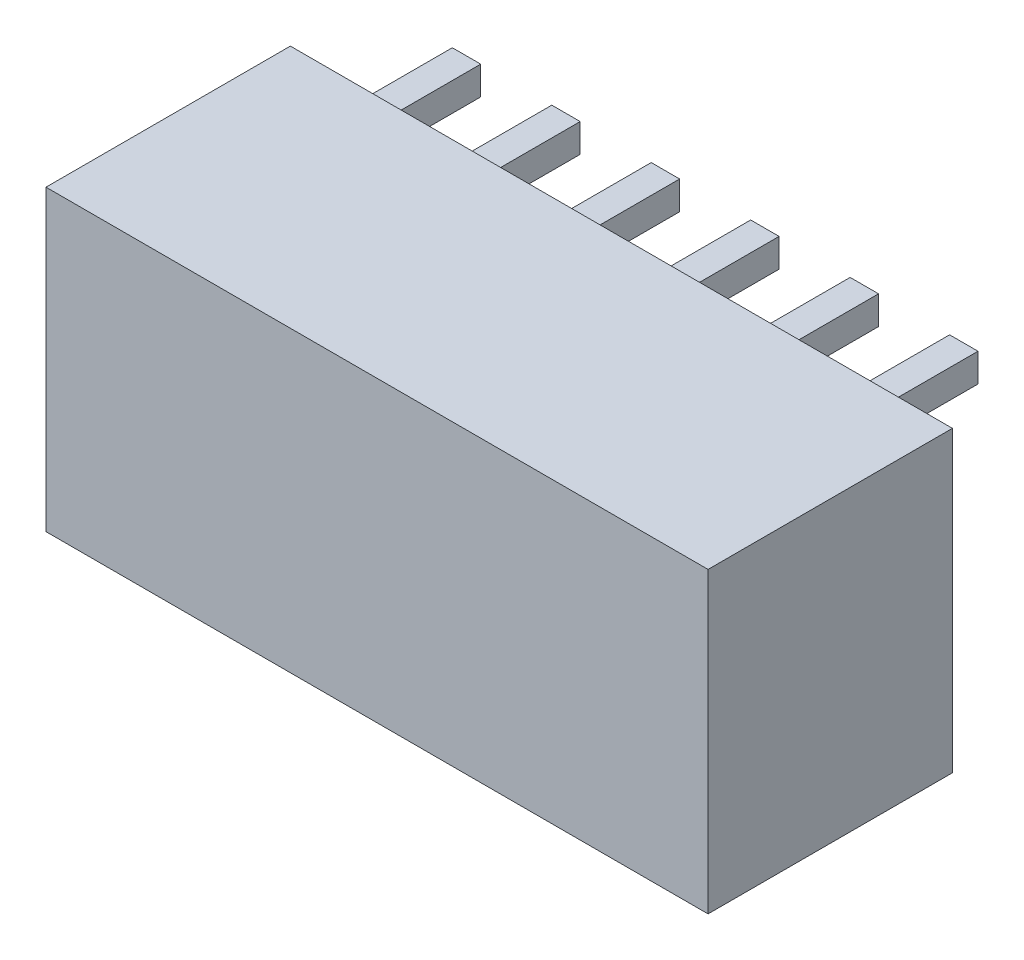
SolidWorks part; units mm, degrees
ref_plane "Спереди" through (0, 0, 0) normal (0, 0, 1) x (1, 0, 0)
ref_plane "Сверху" through (0, 0, 0) normal (0, 1, 0) x (1, 0, 0)
ref_plane "Справа" through (0, 0, 0) normal (1, 0, 0) x (0, 0, -1)
sketch "Эскиз1" plane through (0, 0, 0) normal (0, 0, 1) x (1, 0, 0)
  line L1 (-11.65, -5.25) -> (11.65, -5.25)
  line L2 (-11.65, -5.25) -> (-11.65, 5.25)
  line L3 (-11.65, 5.25) -> (11.65, 5.25)
  line L4 (11.65, -5.25) -> (11.65, 5.25)
  line L5 (-11.65, -5.25) -> (11.65, 5.25) construction
  line L6 (-11.65, 5.25) -> (11.65, -5.25) construction
  point P0 (0, 0)
  dimension "D1" = 23.3
  dimension "D2" = 10.5
extrude "Бобышка-Вытянуть1" add sketch "Эскиз1" along normal blind 8.6
sketch "Эскиз2" plane through (0, -5.25, 0) normal (0, -1, 0) x (1, 0, 0)
  line L0 (-10.65, 6.6) -> (10.65, 6.6)
  line L1 (10.65, 6.6) -> (10.65, 0.2)
  line L2 (10.65, 0.2) -> (8.45, 0.2)
  line L3 (8.45, 0.2) -> (8.45, 1.8)
  line L4 (8.45, 1.8) -> (-6.85, 1.8)
  line L5 (-6.85, 1.8) -> (-6.85, 0.2)
  line L6 (-6.85, 0.2) -> (-9.05, 0.2)
  line L7 (-10.65, 6.6) -> (-10.65, 1.8)
  line L8 (-10.65, 1.8) -> (-9.05, 1.8)
  line L9 (-9.05, 1.8) -> (-9.05, 0.2)
  line L10 (11.65, 8.6) -> (11.65, 0) construction
  line L11 (-11.65, 8.6) -> (-11.65, 0) construction
  line L12 (-11.65, 8.6) -> (11.65, 8.6) construction
  dimension "D1" = 4.8
  dimension "D2" = 6.4
  dimension "D3" = 2.2
  dimension "D4" = 2.2
  dimension "D5" = 3.2
  dimension "D6" = 4.8
  dimension "D7" = 1
  dimension "D8" = 2
extrude "Вырез-Вытянуть1" cut sketch "Эскиз2" against normal blind 7
sketch "Эскиз3" plane through (0, 0, 0) normal (0, 0, -1) x (-1, 0, 0)
  line L0 (11.65, -5.25) -> (-11.65, -5.25) construction
  line L1 (9.25, 4.75) -> (8.25, 4.75)
  line L2 (9.25, 4.75) -> (9.25, 3.75)
  line L3 (9.25, 3.75) -> (8.25, 3.75)
  line L4 (8.25, 4.75) -> (8.25, 3.75)
  line L5 (9.25, 4.75) -> (8.25, 3.75) construction
  line L6 (9.25, 3.75) -> (8.25, 4.75) construction
  line L7 (11.65, 5.25) -> (11.65, -5.25) construction
  point P0 (8.75, 4.25)
  dimension "D1" = 1
  dimension "D2" = 9.5
  dimension "D3" = 2.9
extrude "Бобышка-Вытянуть2" add sketch "Эскиз3" along normal blind 3.6 and the other way blind 5
chamfer "Фаска1" distance 0.3 distance2 0.3 4 edges at (-8.25, 4.25, -3.6) (-8.75, 3.75, -3.6) (-9.25, 4.25, -3.6) (-8.75, 4.75, -3.6)
pattern_linear "Линейный массив1" count 6 spacing 3.5 along (1, 0, 0) of "Бобышка-Вытянуть2", "Фаска1"
equation "\"N\"= 6"
equation "\"D1@Эскиз1\"= ( \"N\" - 1 ) * 3.5 + 5.8"
equation "\"D1@Линейный массив1\"=\"N\""
